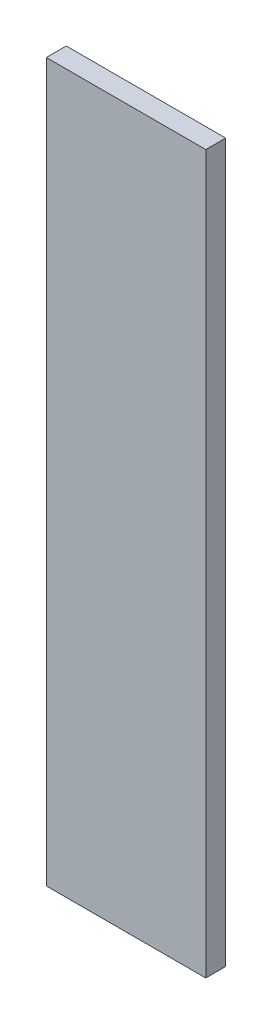
SolidWorks part; units mm, degrees
material "Acrylic (Medium-high impact)"
ref_plane "Front Plane" through (0, 0, 0) normal (0, 0, 1) x (1, 0, 0)
ref_plane "Top Plane" through (0, 0, 0) normal (0, 1, 0) x (1, 0, 0)
ref_plane "Right Plane" through (0, 0, 0) normal (1, 0, 0) x (0, 0, -1)
sketch "Sketch1" plane through (0, 0, 0) normal (0, 0, 1) x (1, 0, 0)
  line L1 (-40, -180) -> (40, -180)
  line L2 (-40, -180) -> (-40, 180)
  line L3 (-40, 180) -> (40, 180)
  line L4 (40, -180) -> (40, 180)
  line L5 (-40, -180) -> (40, 180) construction
  line L6 (-40, 180) -> (40, -180) construction
  point P0 (0, 0)
  dimension "D1" = 80
  dimension "D2" = 360
extrude "Boss-Extrude1" add sketch "Sketch1" along normal blind 10
